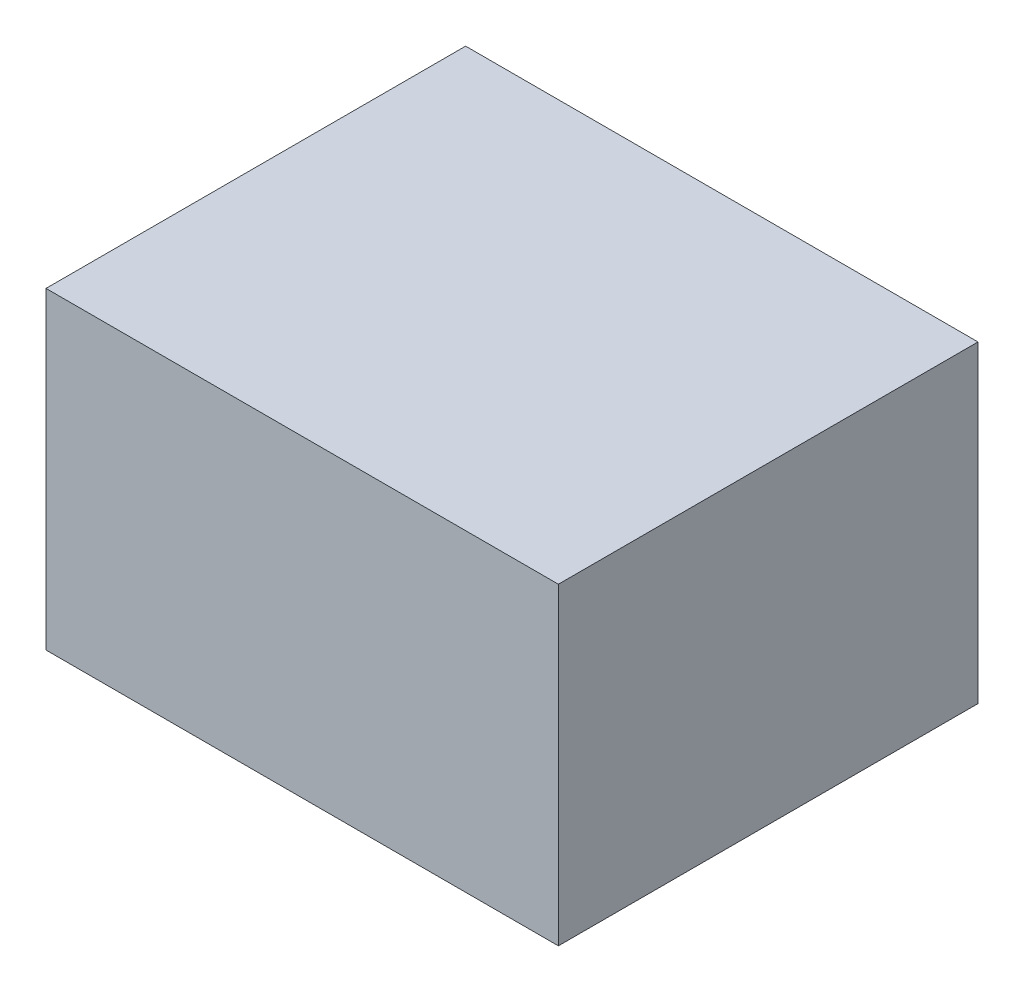
SolidWorks part; units mm, degrees
material "Custom Plastic"
ref_plane "Front Plane" through (0, 0, 0) normal (0, 0, 1) x (1, 0, 0)
ref_plane "Top Plane" through (0, 0, 0) normal (0, 1, 0) x (1, 0, 0)
ref_plane "Right Plane" through (0, 0, 0) normal (1, 0, 0) x (0, 0, -1)
sketch "Sketch1" plane through (0, 0, 0) normal (0, 0, 1) x (1, 0, 0)
  line L1 (6.38, 3.9) -> (-6.38, 3.9)
  line L2 (6.38, 3.9) -> (6.38, -3.9)
  line L3 (6.38, -3.9) -> (-6.38, -3.9)
  line L4 (-6.38, 3.9) -> (-6.38, -3.9)
  point P4 (0, 3.9)
  point P6 (-6.38, 0)
  dimension "D1" = 12.76
  dimension "D2" = 7.8
extrude "Boss-Extrude1" add sketch "Sketch1" along normal blind 10.45
